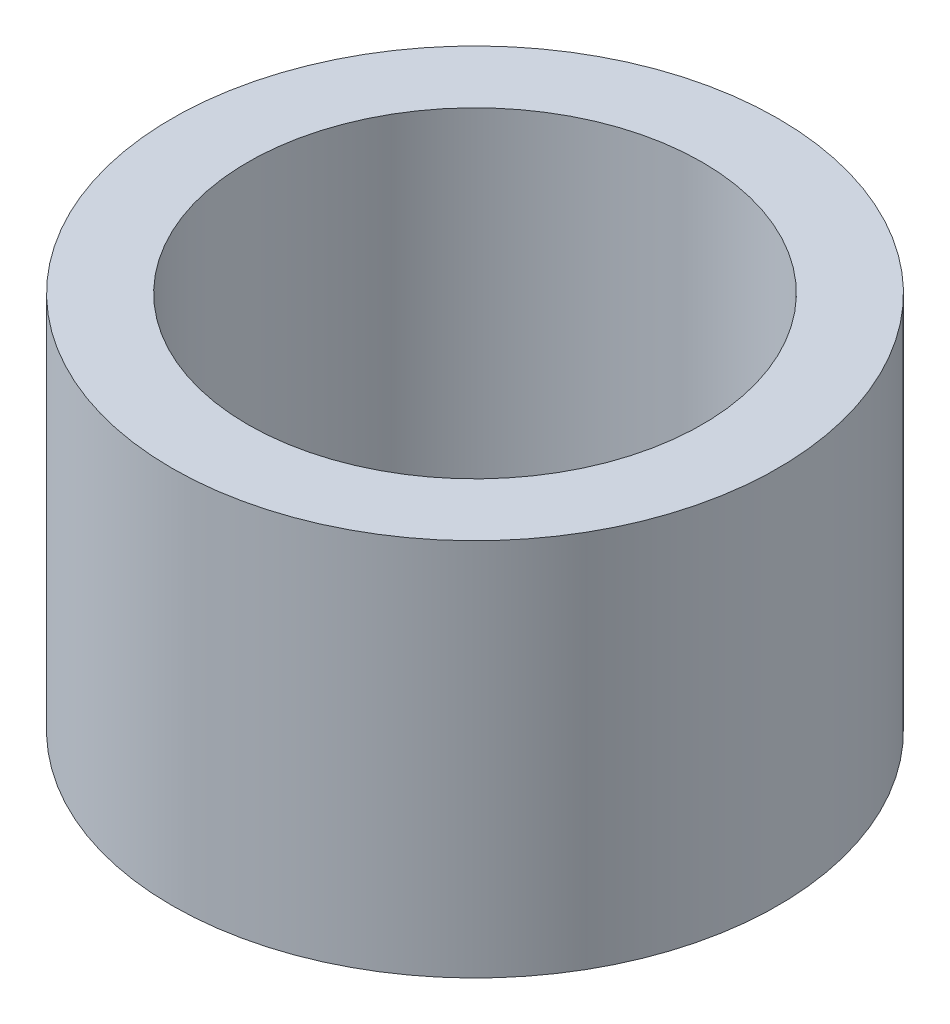
SolidWorks part; units mm, degrees
ref_plane "Спереди" through (0, 0, 0) normal (0, 0, 1) x (1, 0, 0)
ref_plane "Сверху" through (0, 0, 0) normal (0, 1, 0) x (1, 0, 0)
ref_plane "Справа" through (0, 0, 0) normal (1, 0, 0) x (0, 0, -1)
sketch "Эскиз1" plane through (0, 0, 0) normal (0, 1, 0) x (1, 0, 0)
  circle A0 centre (0, 0) radius 3
  circle A1 centre (0, 0) radius 4
  dimension "D1" = 6
  dimension "D2" = 8
extrude "Бобышка-Вытянуть1" add sketch "Эскиз1" along normal blind 5
